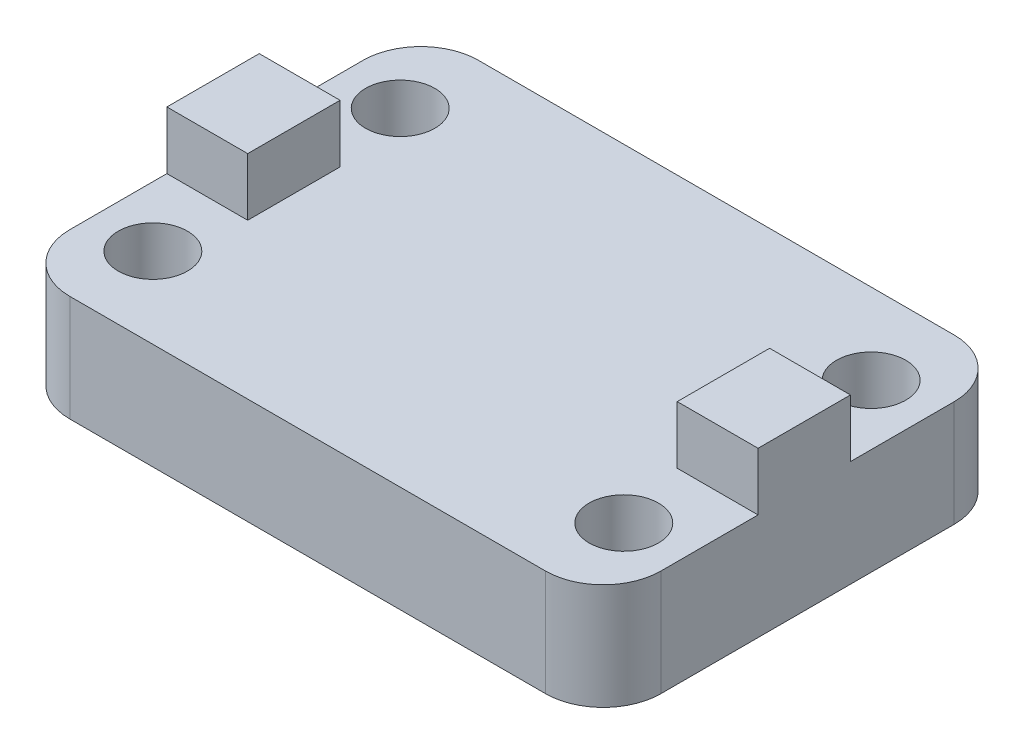
SolidWorks part; units mm, degrees
ref_plane "Front Plane" through (0, 0, 0) normal (0, 0, 1) x (1, 0, 0)
ref_plane "Top Plane" through (0, 0, 0) normal (0, 1, 0) x (1, 0, 0)
ref_plane "Right Plane" through (0, 0, 0) normal (1, 0, 0) x (0, 0, -1)
sketch "Sketch1" plane through (0, 0, 0) normal (0, 1, 0) x (1, 0, 0)
  line L0 (0, -55) -> (0, 55) construction
  line L1 (0, 17.7) -> (25.6, 17.7)
  line L2 (0, 17.7) -> (0, 0)
  line L3 (0, 0) -> (25.6, 0)
  line L4 (25.6, 17.7) -> (25.6, 0)
  line L5 (-55, 0) -> (55, 0) construction
  dimension "D1" = 17.7
  dimension "D2" = 25.6
extrude "Boss-Extrude1" add sketch "Sketch1" along normal blind 4.6 contours L2 L3 L4 L1
fillet "Fillet1" radius 2.5 4 edges at (0, 2.3, 0) (0, 2.3, -17.7) (25.6, 2.3, -17.7) (25.6, 2.3, 0)
sketch "Sketch3" plane through (0, 4.6, 0) normal (0, 1, 0) x (1, 0, 0)
  circle A0 centre (2.6037, 3.4946) radius 1.5
  arc A2 (0, 2.5) -> (2.5, 0) centre (2.5, 2.5) ccw construction
  dimension "D1" = 3
extrude "Cut-Extrude1" cut sketch "Sketch3" against normal through all contours A0
ref_plane "Plane1" through (0, 0, -8.85) normal (0, 0, 1) x (1, 0, 0)
mirror "Mirror1" about plane through (0, 0, -8.85) normal (0, 0, 1) of "Cut-Extrude1"
ref_plane "Plane2" through (12.8, 0, 0) normal (-1, 0, 0) x (0, 0, 1)
mirror "Mirror2" about plane through (12.8, 0, 0) normal (-1, 0, 0) of "Mirror1", "Cut-Extrude1"
sketch "Sketch6" plane through (0, 4.6, 0) normal (0, 1, 0) x (1, 0, 0)
  line L0 (0, -2.53) -> (0, 2.53) construction
  line L1 (0, 10.7054) -> (3.5, 10.7054)
  line L2 (0, 10.7054) -> (0, 6.7054)
  line L3 (0, 6.7054) -> (3.5, 6.7054)
  line L4 (3.5, 10.7054) -> (3.5, 6.7054)
  circle A0 centre (2.6037, 14.2054) radius 1.5 construction
  dimension "D3" = 3.5
  dimension "D1" = 4
  dimension "D2" = 3.5
extrude "Boss-Extrude2" add sketch "Sketch6" along normal blind 2.5
mirror "Mirror3" about plane through (12.8, 0, 0) normal (-1, 0, 0) of "Boss-Extrude2"
